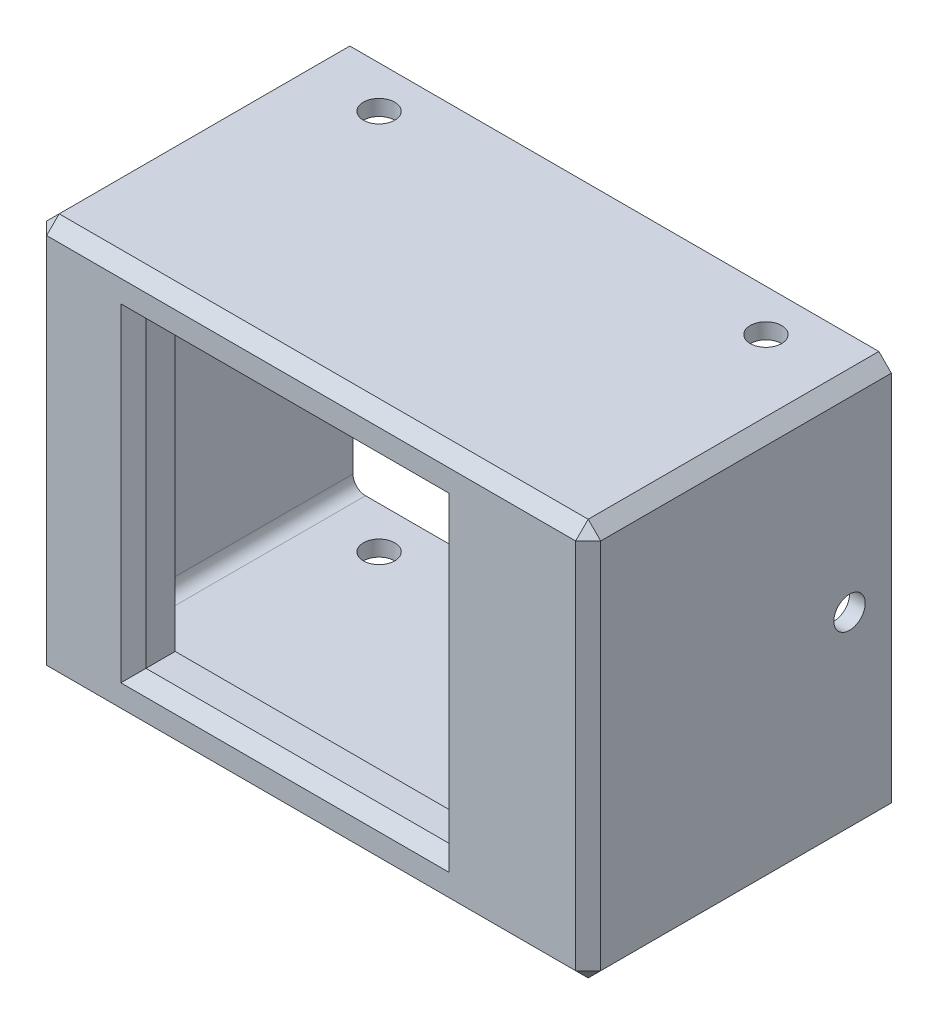
SolidWorks part; units mm, degrees
ref_plane "Plan de face" through (0, 0, 0) normal (0, 0, 1) x (1, 0, 0)
ref_plane "Plan de dessus" through (0, 0, 0) normal (0, 1, 0) x (1, 0, 0)
ref_plane "Plan de droite" through (0, 0, 0) normal (1, 0, 0) x (0, 0, -1)
sketch "Esquisse1" plane through (0, 0, 0) normal (0, 0, 1) x (1, 0, 0)
  line L1 (26.5, 19) -> (-26.5, 19)
  line L2 (26.5, 19) -> (26.5, -19)
  line L3 (26.5, -19) -> (-26.5, -19)
  line L4 (-26.5, 19) -> (-26.5, -19)
  line L5 (26.5, 19) -> (-26.5, -19) construction
  line L6 (26.5, -19) -> (-26.5, 19) construction
  point P0 (0, 0)
  point P6 (0, 0)
  dimension "D1" = 53
  dimension "D2" = 38
extrude "BASE" add sketch "Esquisse1" along normal blind 4
sketch "Esquisse2" plane through (0, 0, 4) normal (0, 0, 1) x (1, 0, 0)
  line L1 (24, 16.5) -> (-24, 16.5) construction
  line L2 (24, 16.5) -> (24, -16.5) construction
  line L3 (24, -16.5) -> (-24, -16.5) construction
  line L4 (-24, 16.5) -> (-24, -16.5) construction
  line L5 (24, 16.5) -> (-24, -16.5) construction
  line L6 (24, -16.5) -> (-24, 16.5) construction
  line L7 (-17, 14.5) -> (12, 14.5)
  line L8 (-17, 14.5) -> (-17, -14.5)
  line L9 (-17, -14.5) -> (12, -14.5)
  line L10 (12, 14.5) -> (12, -14.5)
  point P0 (0, 0)
  dimension "D1" = 33
  dimension "D2" = 48
  dimension "D3" = 7
  dimension "D4" = 2
  dimension "D5" = 2
  dimension "D6" = 12
extrude "Screen" cut sketch "Esquisse2" against normal up to surface (4 mm away) up to face at (0, 0, 0)
sketch "Esquisse5" plane through (0, 0, 0) normal (0, 0, -1) x (-1, 0, 0)
  line L0 (55, 0) -> (-55, 0) construction
  line L1 (24, 16.5) -> (-24, 16.5) construction
  line L2 (24, 16.5) -> (24, -16.5) construction
  line L3 (24, -16.5) -> (-24, -16.5) construction
  line L4 (-24, 16.5) -> (-24, -16.5) construction
  line L5 (24, 16.5) -> (-24, -16.5) construction
  line L6 (24, -16.5) -> (-24, 16.5) construction
  line L7 (0, 55) -> (0, -55) construction
  circle A1 centre (-21, 13.5) radius 2.25
  circle A2 centre (-21, -13.5) radius 2.25
  circle A3 centre (21, -13.5) radius 2.25
  circle A4 centre (21, 13.5) radius 2.25
  point P0 (0, 0)
  dimension "D3" = 4.5
  dimension "D1" = 48
  dimension "D2" = 33
  dimension "D4" = 3
  dimension "D5" = 3
extrude "Inserts_M3" cut sketch "Esquisse5" against normal blind 3
sketch "Esquisse6" plane through (0, 0, 0) normal (0, 0, -1) x (-1, 0, 0)
  line L0 (-25, 17.5) -> (-25, -17.5)
  line L1 (-26.5, 19) -> (26.5, 19)
  line L2 (-26.5, 19) -> (-26.5, -19)
  line L3 (-26.5, -19) -> (26.5, -19)
  line L4 (26.5, 19) -> (26.5, -19)
  line L5 (-25, -17.5) -> (25, -17.5)
  line L6 (25, 17.5) -> (25, -17.5)
  line L7 (-25, 17.5) -> (25, 17.5)
  dimension "D1" = 1.5
extrude "Walls" add sketch "Esquisse6" along normal blind 25
chamfer "Chanfrein_EXT" distance 1.2 angle 45 12 edges at (-2.5, 14.5, 4) (-17, 0, 4) (-2.5, -14.5, 4) (12, 0, 4) (0, 19, 4) (26.5, 19, -10.5) (26.5, 0, 4) (26.5, -19, -10.5) (0, -19, 4) (-26.5, -19, -10.5) (-26.5, 0, 4) (-26.5, 19, -10.5)
fillet "Congé1" radius 1.2 8 edges at (0, 17.5, 0) (25, 0, 0) (-25, 0, 0) (0, -17.5, 0) (-25, -17.5, -12.5) (-25, 17.5, -12.5) (25, -17.5, -12.5) (25, 17.5, -12.5)
sketch "Esquisse7" plane through (26.5, 0, 0) normal (1, 0, 0) x (0, 0, -1)
  line L0 (25, 17.8) -> (25, -17.8) construction
  line L1 (-2.8, 17.8) -> (-2.8, -17.8) construction
  circle A0 centre (21, 0) radius 1.5
  point P4 (0, 0)
  point P7 (-2.8, 0)
  dimension "D1" = 3
  dimension "D2" = 4
extrude "Passage_Vis_Horizontal" cut sketch "Esquisse7" against normal through all
sketch "Esquisse9" plane through (0, 19, 0) normal (0, 1, 0) x (1, 0, 0)
  line L0 (-25.3, 25) -> (25.3, 25) construction
  line L1 (-26.5, -2.8) -> (-26.5, 25) construction
  line L2 (26.5, 25) -> (26.5, -2.8) construction
  circle A0 centre (-18.5, 21) radius 1.5
  circle A1 centre (18.5, 21) radius 1.5
  point P4 (-18.3928, 13.9696)
  dimension "D1" = 3
  dimension "D2" = 4
  dimension "D3" = 8
  dimension "D4" = 8
extrude "Passage_Vis_Vertical" cut sketch "Esquisse9" against normal through all
